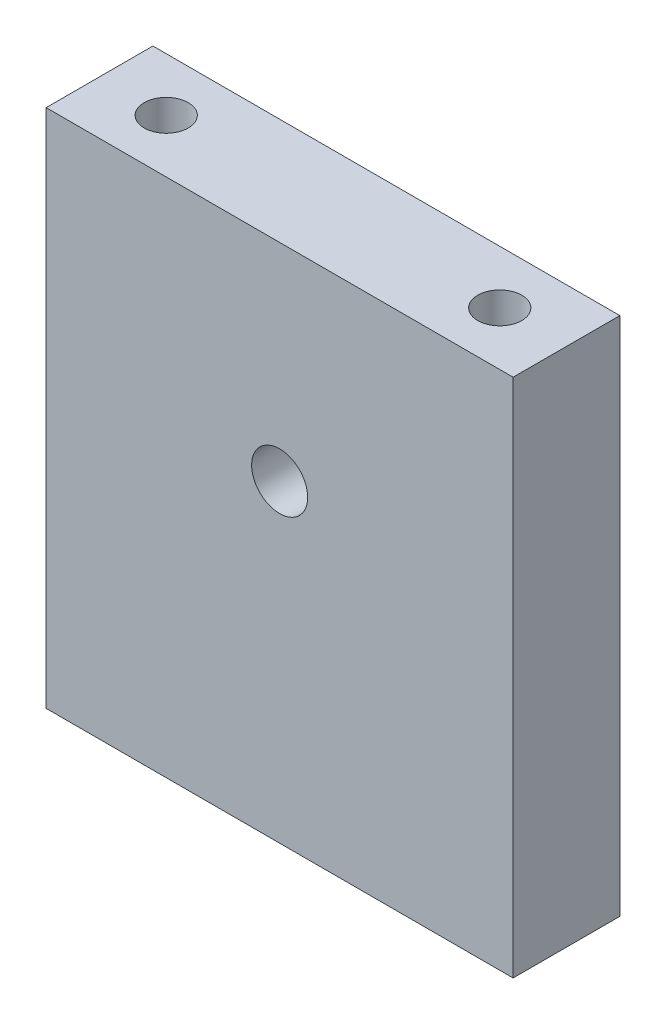
SolidWorks part; units mm, degrees
material "6061-T6 (SS)"
ref_plane "前视基准面" through (0, 0, 0) normal (0, 0, 1) x (1, 0, 0)
ref_plane "上视基准面" through (0, 0, 0) normal (0, 1, 0) x (1, 0, 0)
ref_plane "右视基准面" through (0, 0, 0) normal (1, 0, 0) x (0, 0, -1)
sketch "草图1" plane through (0, 0, 0) normal (0, 0, 1) x (1, 0, 0)
  line L0 (17.5, 39) -> (17.5, 23.5) construction
  line L1 (0, 0) -> (35, 0)
  line L2 (0, 0) -> (0, 39)
  line L3 (0, 39) -> (35, 39)
  line L4 (35, 0) -> (35, 39)
  circle A0 centre (17.5, 23.5) radius 2.1
  dimension "D3" = 4.2
  dimension "D1" = 39
  dimension "D2" = 35
  dimension "D4" = 15.5
extrude "凸台-拉伸1" add sketch "草图1" along normal blind 8
cosmetic thread "装饰螺纹线5" parameters "D2"=5
sketch "草图2" plane through (0, 39, 0) normal (0, 1, 0) x (1, 0, 0)
  line L0 (0, -4) -> (5, -4) construction
  line L1 (0, -8) -> (0, 0) construction
  line L2 (5, -4) -> (30, -4) construction
  line L3 (30, -4) -> (35, -4) construction
  line L4 (35, -8) -> (35, 0) construction
  circle A0 centre (5, -4) radius 1.65
  circle A1 centre (30, -4) radius 1.65
  dimension "D2" = 3.3
  dimension "D1" = 25
extrude "切除-拉伸1" cut sketch "草图2" against normal through all
cosmetic thread "装饰螺纹线1" parameters "D2"=4
cosmetic thread "装饰螺纹线2" parameters "D2"=4
cosmetic thread "装饰螺纹线3" parameters "D2"=4
cosmetic thread "装饰螺纹线4" parameters "D2"=4
